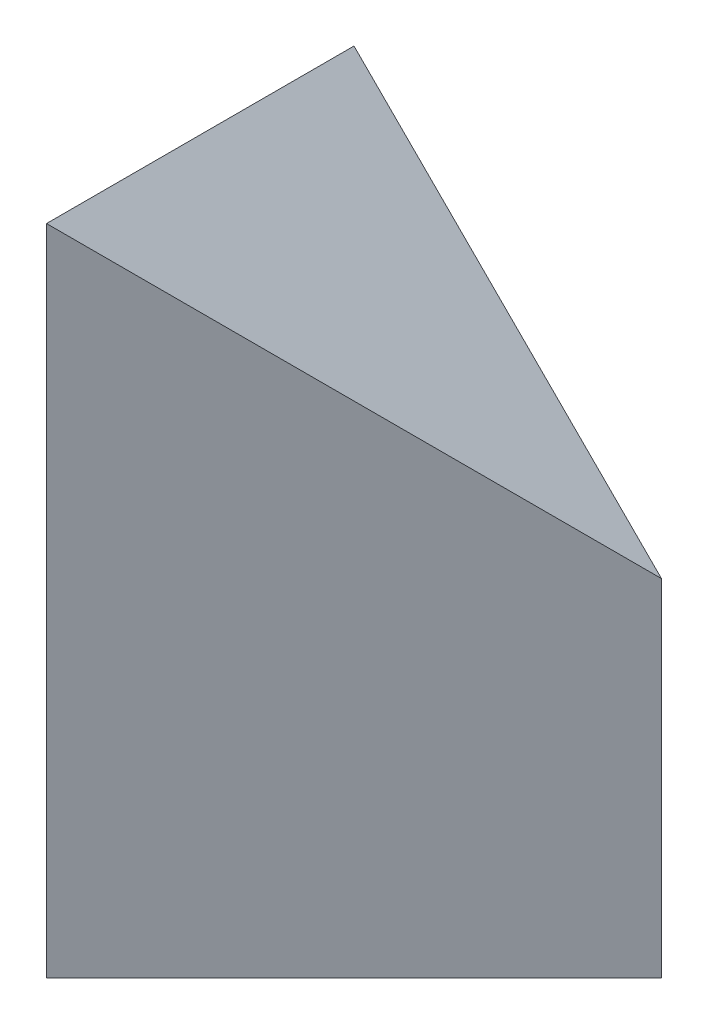
SolidWorks part; units mm, degrees
ref_plane "Front Plane" through (0, 0, 0) normal (0, 0, 1) x (1, 0, 0)
ref_plane "Top Plane" through (0, 0, 0) normal (0, 1, 0) x (1, 0, 0)
ref_plane "Right Plane" through (0, 0, 0) normal (1, 0, 0) x (0, 0, -1)
sketch "Sketch1" plane through (0, 0, 0) normal (0, 1, 0) x (1, 0, 0)
  line L0 (50.8, 25.4) -> (0, 25.4)
  line L1 (0, 25.4) -> (0, -25.4)
  line L2 (0, -25.4) -> (50.8, 25.4)
  dimension "D1" = 50.8
  dimension "D2" = 50.8
extrude "Boss-Extrude1" add sketch "Sketch1" along normal blind 107.95
sketch "Sketch2" plane through (0, 0, 0) normal (0, 0, 1) x (1, 0, 0)
  line L0 (0, 107.95) -> (50.8, 57.15)
  line L1 (50.8, 107.95) -> (50.8, 0) construction
  line L2 (0, 107.95) -> (0, 0) construction
  dimension "D1" = 45
extrude "Cut-Extrude1" cut sketch "Sketch2" against normal through all and the other way through all
